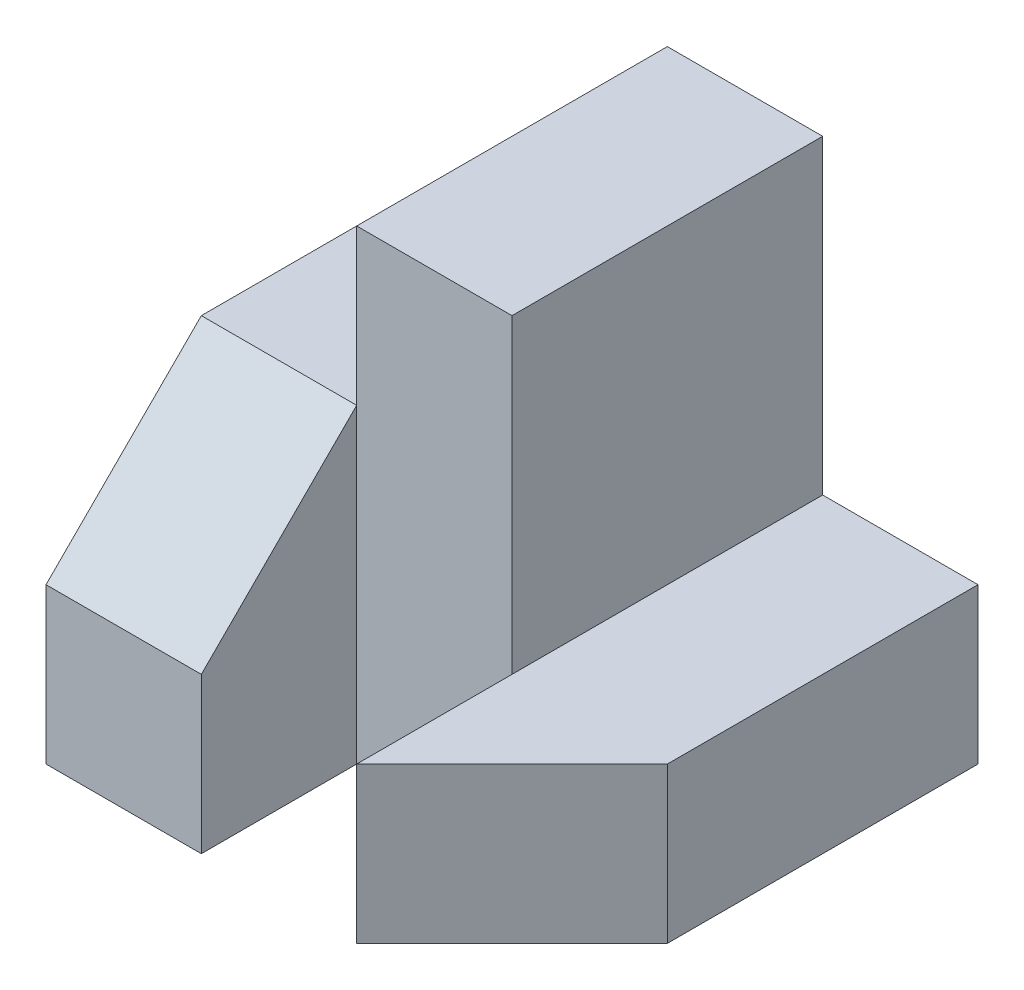
SolidWorks part; units mm, degrees
ref_plane "前基準面" through (0, 0, 0) normal (0, 0, 1) x (1, 0, 0)
ref_plane "上基準面" through (0, 0, 0) normal (0, 1, 0) x (1, 0, 0)
ref_plane "右基準面" through (0, 0, 0) normal (1, 0, 0) x (0, 0, -1)
sketch "草圖1" plane through (0, 0, 0) normal (0, 0, 1) x (1, 0, 0)
  line L1 (0, 0) -> (30, 0)
  line L2 (0, 0) -> (0, 30)
  line L3 (0, 30) -> (30, 30)
  line L4 (30, 0) -> (30, 30)
  dimension "D1" = 30
  dimension "D2" = 30
extrude "填料-伸1" add sketch "草圖1" against normal blind 30
sketch "草圖30" plane through (0, 0, 0) normal (0, 0, 1) x (1, 0, 0)
  line L1 (0, 30) -> (10, 30)
  line L2 (0, 30) -> (0, 20)
  line L3 (0, 20) -> (10, 20)
  line L4 (10, 30) -> (10, 20)
  line L5 (30, 30) -> (20, 30)
  line L6 (30, 30) -> (30, 10)
  line L7 (30, 10) -> (20, 10)
  line L8 (20, 30) -> (20, 10)
  dimension "D1" = 10
  dimension "D2" = 10
  dimension "D3" = 10
  dimension "D4" = 20
extrude "除料-伸長20" cut sketch "草圖30" against normal through all
sketch "草圖32" plane through (20, 0, 0) normal (1, 0, 0) x (0, 0, -1)
  line L0 (10, 20) -> (0, 10)
  line L1 (0, 30) -> (10, 30)
  line L2 (0, 30) -> (0, 20)
  line L3 (0, 20) -> (10, 20)
  line L4 (10, 30) -> (10, 20)
  line L5 (0, 30) -> (0, 10) construction
  line L6 (0, 10) -> (0, 20)
  line M3 (0, 30) -> (0, 10)
  line M6 (30, 30) -> (0, 30)
  dimension "D1" = 10
  dimension "D2" = 10
  dimension "D3" = 10
extrude "除料-伸長21" cut sketch "草圖32" against normal through all contours L4 L3 M6 M3 | L3 L0 M3
sketch "草圖33" plane through (0, 30, 0) normal (0, 1, 0) x (1, 0, 0)
  line L0 (-16.5, 0) -> (16.5, 0) construction
  line L1 (10, 10) -> (20, 10)
  line L2 (10, 10) -> (10, 0)
  line L3 (10, 0) -> (20, 0)
  line L4 (20, 10) -> (20, 0)
  line L5 (20, 30) -> (20, 0) construction
  line L6 (30, 10) -> (20, 0)
  line L7 (30, 30) -> (30, 0) construction
  line L8 (30, 10) -> (30, 0)
  line L9 (20, 0) -> (30, 0)
  line M6 (10, 10) -> (20, 10)
  dimension "D1" = 10
  dimension "D2" = 10
  dimension "D3" = 10
  dimension "D4" = 45
extrude "除料-伸長22" cut sketch "草圖33" against normal through all contours L4 L2 L3 M6 | L6 L9 L8
